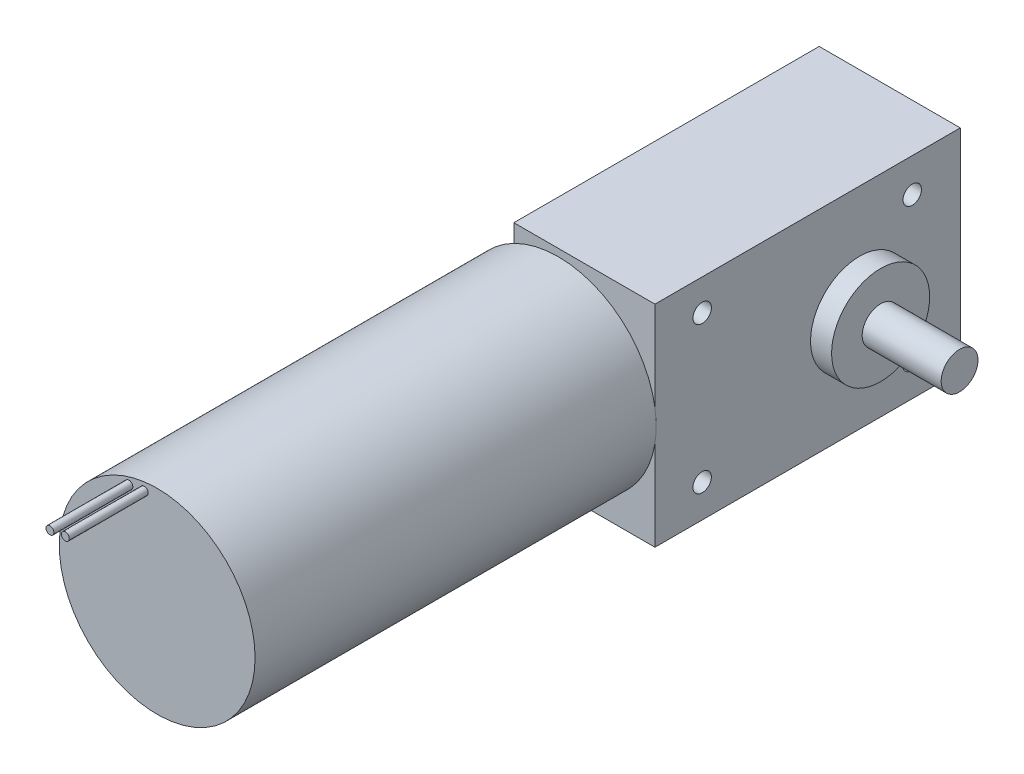
SolidWorks part; units mm, degrees
ref_plane "Front Plane" through (0, 0, 0) normal (0, 0, 1) x (1, 0, 0)
ref_plane "Top Plane" through (0, 0, 0) normal (0, 1, 0) x (1, 0, 0)
ref_plane "Right Plane" through (0, 0, 0) normal (1, 0, 0) x (0, 0, -1)
sketch "Sketch4" plane through (0, 0, 0) normal (0, 0, 1) x (1, 0, 0)
  circle A0 centre (-63.8569, 21.8657) radius 18.6
  dimension "D1" = 37.2
extrude "Boss-Extrude3" add sketch "Sketch4" along normal blind 76.2
sketch "Sketch5" plane through (0, 0, 76.2) normal (0, 0, 1) x (1, 0, 0)
  circle A0 centre (-66.3053, 38.8201) radius 0.75
  point P2 (0, 0)
  dimension "D1" = 1.5
extrude "Boss-Extrude4" add sketch "Sketch5" along normal blind 15
sketch "Sketch6" plane through (0, 0, 76.2) normal (0, 0, 1) x (1, 0, 0)
  circle A0 centre (-69.2249, 38.365) radius 0.75
  dimension "D1" = 1.5
extrude "Boss-Extrude5" add sketch "Sketch6" along normal blind 15
sketch "Sketch7" plane through (0, 0, 0) normal (0, 0, -1) x (-1, 0, 0)
  line L1 (72.2953, 41.836) -> (45.4953, 41.836)
  line L2 (72.2953, 41.836) -> (72.2953, 1.836)
  line L3 (72.2953, 1.836) -> (45.4953, 1.836)
  line L4 (45.4953, 41.836) -> (45.4953, 1.836)
  dimension "D1" = 26.8
  dimension "D2" = 40
extrude "Boss-Extrude6" add sketch "Sketch7" along normal blind 58
sketch "Sketch8" plane through (-72.2953, 0, 0) normal (-1, 0, 0) x (0, 0, 1)
  line L0 (-58, 41.836) -> (0, 41.836) construction
  line L1 (-58, 1.836) -> (-58, 41.836) construction
  circle A0 centre (-48.85, 35.536) radius 1.75
  dimension "D1" = 3.5
  dimension "D2" = 6.3
  dimension "D3" = 9.15
extrude "Cut-Extrude1" cut sketch "Sketch8" against normal blind 5
sketch "Sketch9" plane through (-72.2953, 0, 0) normal (-1, 0, 0) x (0, 0, 1)
  line L0 (-58, 41.836) -> (0, 41.836) construction
  line L1 (0, 5.29) -> (0, 38.4413) construction
  circle A0 centre (-9.15, 35.536) radius 1.75
  point P6 (0, 0)
  point P7 (0, 0)
  dimension "D1" = 3.5
  dimension "D2" = 6.3
  dimension "D3" = 9.15
extrude "Cut-Extrude2" cut sketch "Sketch9" against normal blind 5
sketch "Sketch10" plane through (-72.2953, 0, 0) normal (-1, 0, 0) x (0, 0, 1)
  line L0 (-58, 1.836) -> (-58, 41.836) construction
  line L1 (-58, 1.836) -> (0, 1.836) construction
  circle A0 centre (-48.85, 6.776) radius 1.75
  point P6 (0, 0)
  dimension "D1" = 3.5
  dimension "D2" = 9.15
  dimension "D3" = 4.94
extrude "Cut-Extrude3" cut sketch "Sketch10" against normal blind 5
sketch "Sketch11" plane through (-72.2953, 0, 0) normal (-1, 0, 0) x (0, 0, 1)
  line L0 (-58, 1.836) -> (0, 1.836) construction
  line L1 (0, 5.29) -> (0, 38.4413) construction
  circle A0 centre (-9.15, 6.776) radius 1.75
  dimension "D1" = 3.5
  dimension "D2" = 4.94
  dimension "D3" = 9.15
extrude "Cut-Extrude4" cut sketch "Sketch11" against normal blind 5
sketch "Sketch12" plane through (-72.2953, 0, 0) normal (-1, 0, 0) x (0, 0, 1)
  line L0 (-58, 1.836) -> (-58, 41.836) construction
  line L2 (-58, 1.836) -> (0, 1.836) construction
  circle A0 centre (-38.6, 21.236) radius 9.4
  dimension "D1" = 18.8
  dimension "D2" = 19.4
  dimension "D3" = 19.4
extrude "Boss-Extrude7" add sketch "Sketch12" along normal blind 4
sketch "Sketch13" plane through (-45.4953, 0, 0) normal (1, 0, 0) x (0, 0, -1)
  line L0 (58, 41.836) -> (0, 41.836) construction
  line L1 (0, 41.836) -> (0, 24.8344) construction
  circle A0 centre (8.97, 35.916) radius 1.75
  dimension "D1" = 3.5
  dimension "D2" = 5.92
  dimension "D3" = 8.97
extrude "Cut-Extrude5" cut sketch "Sketch13" against normal blind 10
sketch "Sketch14" plane through (-45.4953, 0, 0) normal (1, 0, 0) x (0, 0, -1)
  line L0 (0, 18.8969) -> (0, 1.836) construction
  line L1 (58, 1.836) -> (0, 1.836) construction
  circle A0 centre (8.97, 8.066) radius 1.75
  dimension "D1" = 3.5
  dimension "D2" = 8.97
  dimension "D3" = 6.23
extrude "Cut-Extrude6" cut sketch "Sketch14" against normal blind 10
sketch "Sketch17" plane through (-45.4953, 0, 0) normal (1, 0, 0) x (0, 0, -1)
  line L0 (58, 41.836) -> (58, 1.836) construction
  line L1 (58, 1.836) -> (0, 1.836) construction
  circle A0 centre (48.78, 8.266) radius 1.75
  dimension "D1" = 3.5
  dimension "D2" = 9.22
  dimension "D3" = 6.43
extrude "Cut-Extrude7" cut sketch "Sketch17" against normal blind 10
sketch "Sketch18" plane through (-45.4953, 0, 0) normal (1, 0, 0) x (0, 0, -1)
  line L0 (58, 41.836) -> (0, 41.836) construction
  line L1 (58, 41.836) -> (58, 1.836) construction
  circle A0 centre (48.88, 35.406) radius 1.75
  dimension "D1" = 3.5
  dimension "D2" = 6.43
  dimension "D3" = 9.12
extrude "Cut-Extrude8" cut sketch "Sketch18" against normal blind 10
sketch "Sketch19" plane through (-45.4953, 0, 0) normal (1, 0, 0) x (0, 0, -1)
  line L0 (58, 1.836) -> (0, 1.836) construction
  line L1 (58, 41.836) -> (58, 1.836) construction
  circle A0 centre (38.87, 20.966) radius 9.315
  dimension "D1" = 18.63
  dimension "D2" = 19.13
  dimension "D3" = 19.13
extrude "Boss-Extrude8" add sketch "Sketch19" along normal blind 4
sketch "Sketch21" plane through (-41.4953, 0, 0) normal (1, 0, 0) x (0, 0, -1)
  circle A0 centre (38.87, 20.966) radius 3.5
  circle A1 centre (38.87, 20.966) radius 9.315 construction
  dimension "D1" = 7
  dimension "D2" = 0
extrude "Boss-Extrude9" add sketch "Sketch21" along normal blind 15
